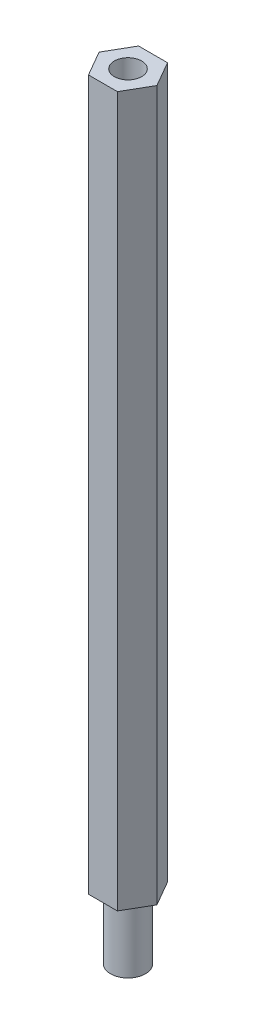
SolidWorks part; units mm, degrees
ref_plane "前视基准面" through (0, 0, 0) normal (0, 0, 1) x (1, 0, 0)
ref_plane "上视基准面" through (0, 0, 0) normal (0, 1, 0) x (1, 0, 0)
ref_plane "右视基准面" through (0, 0, 0) normal (1, 0, 0) x (0, 0, -1)
sketch "草图4" plane through (0, 0, 0) normal (0, 1, 0) x (1, 0, 0)
  line L0 (-12.7945, 0) -> (16.3015, 0) construction
  line L2 (1.325, -2.295) -> (2.65, 0)
  line L3 (2.65, 0) -> (1.325, 2.295)
  line L4 (1.325, 2.295) -> (-1.325, 2.295)
  line L5 (-1.325, 2.295) -> (-2.65, 0)
  line L6 (-2.65, 0) -> (-1.325, -2.295)
  line L7 (-1.325, -2.295) -> (1.325, -2.295)
  circle A0 centre (0, 0) radius 2.295 construction
  dimension "D1" = 5.3
extrude "凸台-拉伸1" add sketch "草图4" along normal blind 65
sketch "草图6" plane through (0, 0, 0) normal (0, -1, 0) x (-1, 0, 0)
  circle A0 centre (0, 0) radius 1.6
  dimension "D1" = 3.2
extrude "凸台-拉伸2" add sketch "草图6" along normal blind 6
cosmetic thread "装饰螺纹线1"
sketch "草图7" plane through (0, 65, 0) normal (0, 1, 0) x (1, 0, 0)
  circle A0 centre (0, 0) radius 1.25
  dimension "D1" = 2.5
extrude "切除-拉伸1" cut sketch "草图7" against normal blind 5
cosmetic thread "装饰螺纹线2" parameters "D2"=3
